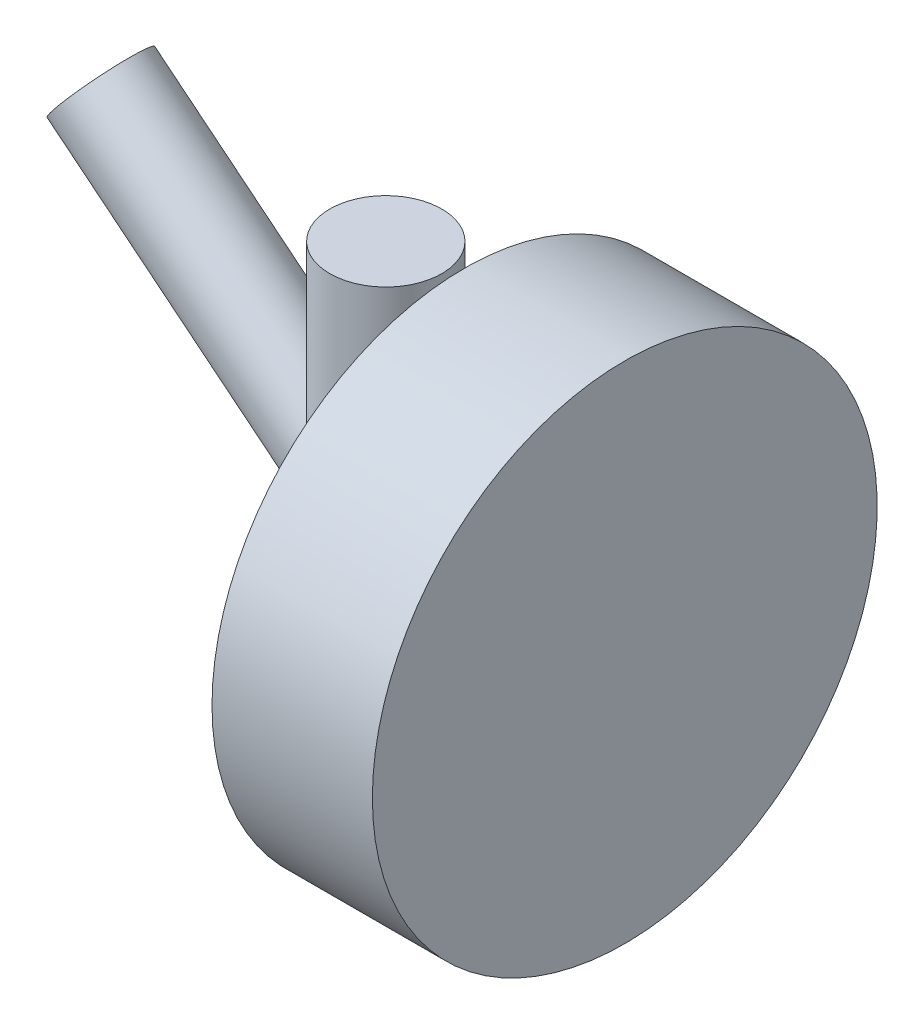
SolidWorks part; units mm, degrees
ref_plane "Front Plane" through (0, 0, 0) normal (0, 0, 1) x (1, 0, 0)
ref_plane "Top Plane" through (0, 0, 0) normal (0, 1, 0) x (1, 0, 0)
ref_plane "Right Plane" through (0, 0, 0) normal (1, 0, 0) x (0, 0, -1)
sketch "Sketch1" plane through (0, 0, 0) normal (1, 0, 0) x (0, 0, -1)
  circle A0 centre (0, 0) radius 314.7949
  dimension "D1" = 629.5898
extrude "Boss-Extrude1" add sketch "Sketch1" along normal mid plane 199.9996
ref_plane "Plane1" through (0, -314.7949, 0) normal (0, -1, 0) x (-1, 0, 0)
sketch "Sketch2" plane through (0, -314.7949, 0) normal (0, 1, 0) x (1, 0, 0)
  line L0 (-99.9998, 314.7949) -> (-99.9998, -314.7949) construction
  circle A0 centre (-198.0692, 0) radius 69.85
  dimension "D1" = 139.7
  dimension "D2" = 98.0694
extrude "Boss-Extrude2" add sketch "Sketch2" along normal blind 457.2 from offset 152.4 separate body
sketch "Sketch3" plane through (0, 0, 0) normal (0, 0, 1) x (1, 0, 0)
  line L0 (-198.0692, 294.8051) -> (-198.0692, -162.3949) construction
  line L1 (-128.2192, 294.8051) -> (-267.9192, 294.8051) construction
  line L2 (-267.9192, -162.3949) -> (-128.2192, -162.3949) construction
  line L3 (-198.0692, 1.6383) -> (-553.3803, 289.3636)
  line L4 (-109.9998, -314.7949) -> (109.9998, -314.7949) construction
  dimension "D1" = 316.4332
  dimension "D2" = 51
  dimension "D3" = 457.2
ref_plane "Plane2" through (-553.3803, 289.3636, 0) normal (-0.7771, 0.6293, 0) x (0, 0, 1)
sketch "Sketch4" plane through (-553.3803, 289.3636, 0) normal (-0.7771, 0.6293, 0) x (0, 0, 1)
  circle A0 centre (0, 0) radius 56.896
  dimension "D1" = 113.792
sweep "Sweep1" add profiles "Sketch4" path "Sketch3"
equation "\"PRIMER_USAGE\"= ( \"SW-SurfaceArea\" / 144 ) / 135"
equation "\"WET_PAINT_USAGE\"= ( \"SW-SurfaceArea\" / 144 ) / 125"
equation "\"POWDERCOAT_USAGE\"= ( \"SW-SurfaceArea\" / 144 ) / 29.79"
equation "\"DECKOVER_USAGE\"= ( \"SW-SurfaceArea\" / 144 ) / 75"
equation "\"SW_NON-SKID\"= ( \"SW-SurfaceArea\" / 144 ) / 165"
equation "\"TYPE_1_ANODIZATING\"= ( \"SW-SurfaceArea\" * 0.0001 )"
equation "\"TYPE_2_ANODIZING\"= ( \"SW-SurfaceArea\" * 0.0005 )"
equation "\"TYPE_3_ANODIZING-HARDCOAT\"= ( \"SW-SurfaceArea\" * 0.003 )"
